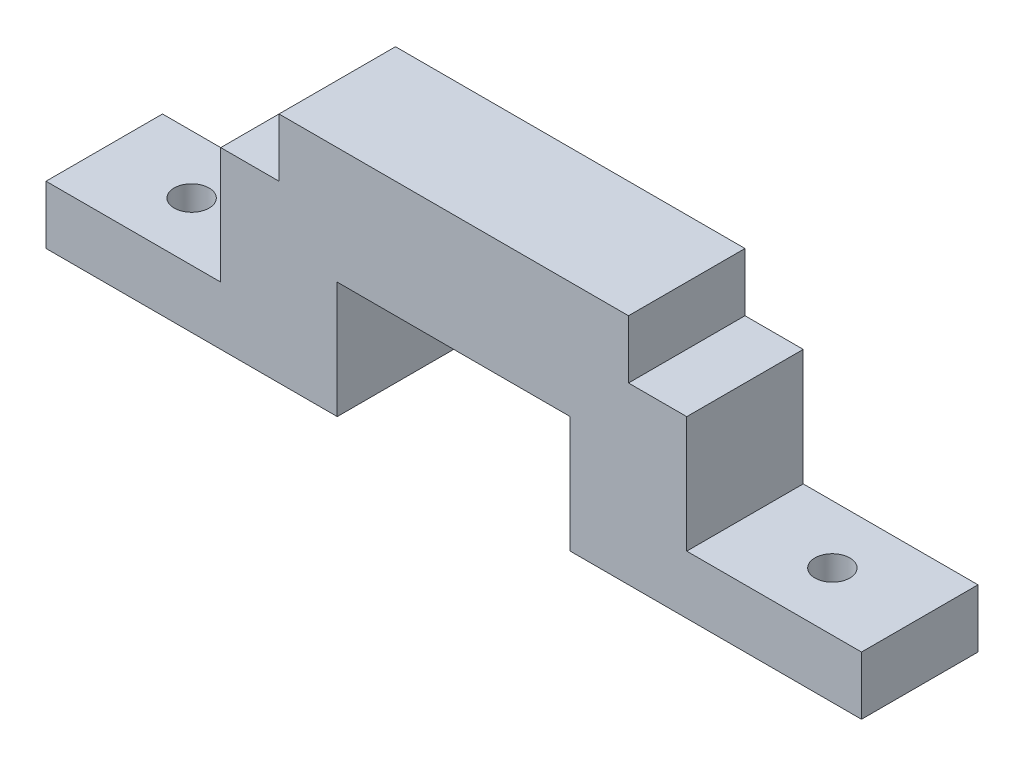
SolidWorks part; units mm, degrees
ref_plane "前视基准面" through (0, 0, 0) normal (0, 0, 1) x (1, 0, 0)
ref_plane "上视基准面" through (0, 0, 0) normal (0, 1, 0) x (1, 0, 0)
ref_plane "右视基准面" through (0, 0, 0) normal (1, 0, 0) x (0, 0, -1)
sketch "草图1" plane through (0, 0, 0) normal (0, 0, 1) x (1, 0, 0)
  line L0 (-20, 0) -> (-10, 0)
  line L1 (-10, 0) -> (-10, 10)
  line L2 (-10, 10) -> (10, 10)
  line L3 (10, 10) -> (10, 0)
  line L4 (10, 0) -> (20, 0)
  line L5 (20, 5) -> (20, 15)
  line L6 (15, 20) -> (-15, 20)
  line L7 (-20, 15) -> (-20, 5)
  line L8 (-20, 15) -> (-15, 15)
  line L9 (-15, 15) -> (-15, 20)
  line L10 (15, 20) -> (15, 15)
  line L11 (15, 15) -> (20, 15)
  line L12 (-20, 5) -> (-35, 5)
  line L13 (-35, 5) -> (-35, 0)
  line L14 (-35, 0) -> (-20, 0)
  line L15 (20, 5) -> (35, 5)
  line L16 (35, 5) -> (35, 0)
  line L17 (35, 0) -> (20, 0)
  dimension "D1" = 20
  dimension "D2" = 10
  dimension "D3" = 10
  dimension "D4" = 15
  dimension "D5" = 40
  dimension "D6" = 20
  dimension "D7" = 30
  dimension "D8" = 15
  dimension "D9" = 5
  dimension "D10" = 15
  dimension "D11" = 15
  dimension "D12" = 5
extrude "凸台-拉伸1" add sketch "草图1" along normal blind 10
sketch "草图2" plane through (0, 5, 0) normal (0, 1, 0) x (1, 0, 0)
  circle A0 centre (-27.5, -5) radius 1.5
  circle A1 centre (27.5, -5) radius 1.5
  dimension "D1" = 55
  dimension "D2" = 3
  dimension "D3" = 3
  dimension "D4" = 5
  dimension "D5" = 27.5
  dimension "D6" = 27.5
extrude "切除-拉伸1" cut sketch "草图2" against normal through all both and the other way through all
